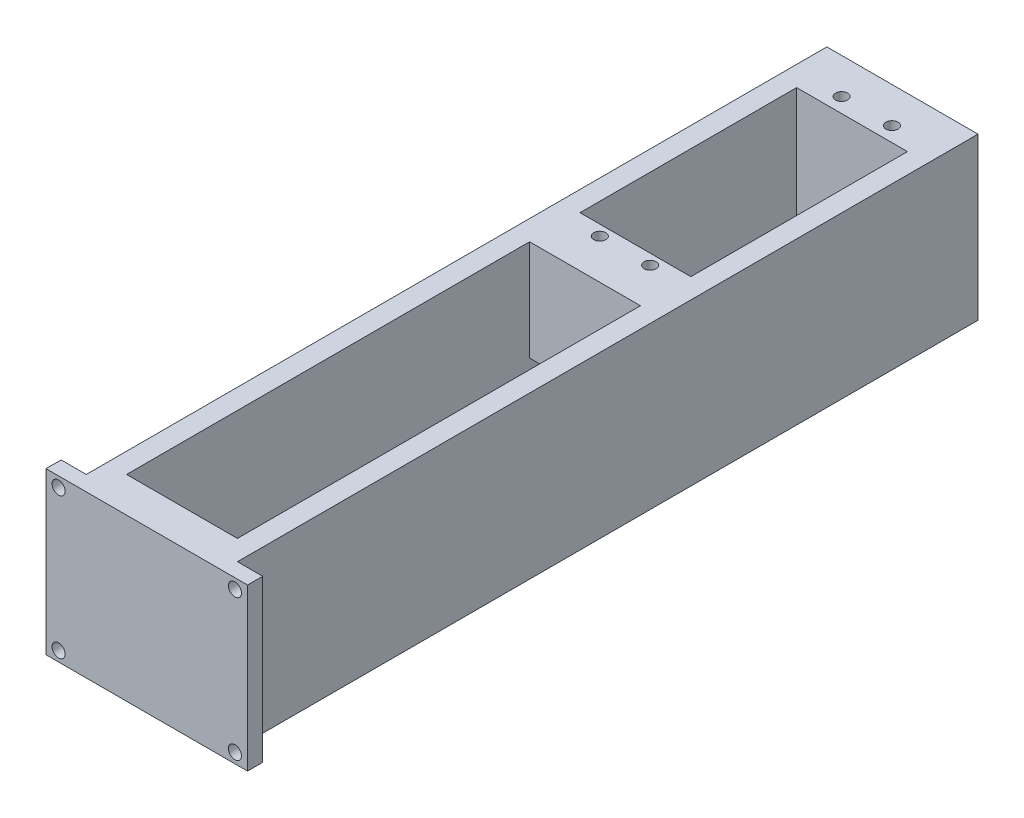
SolidWorks part; units mm, degrees
ref_plane "Front Plane" through (0, 0, 0) normal (0, 0, 1) x (1, 0, 0)
ref_plane "Top Plane" through (0, 0, 0) normal (0, 1, 0) x (1, 0, 0)
ref_plane "Right Plane" through (0, 0, 0) normal (1, 0, 0) x (0, 0, -1)
sketch "Sketch1" plane through (0, 0, 0) normal (0, 1, 0) x (1, 0, 0)
  line L1 (0, 0) -> (30, 0)
  line L2 (0, 0) -> (0, 150)
  line L3 (0, 150) -> (30, 150)
  line L4 (30, 0) -> (30, 150)
  dimension "D1" = 30
  dimension "D2" = 150
extrude "Boss-Extrude1" add sketch "Sketch1" along normal blind 40
sketch "Sketch2" plane through (0, 40, 0) normal (0, 1, 0) x (1, 0, 0)
  line L0 (30, 150) -> (0, 150) construction
  line L1 (4, 140) -> (26, 140)
  line L2 (4, 140) -> (4, 97)
  line L3 (4, 97) -> (26, 97)
  line L4 (26, 140) -> (26, 97)
  line L5 (0, 150) -> (0, 0) construction
  dimension "D1" = 22
  dimension "D2" = 43
  dimension "D3" = 10
  dimension "D4" = 4
extrude "Cut-Extrude1" cut sketch "Sketch2" against normal blind 30 and the other way through all
sketch "Sketch4" plane through (0, 0, 0) normal (0, -1, 0) x (1, 0, 0)
  line L0 (4, -140) -> (4, -97) construction
  line L1 (4, -97) -> (26, -97)
  line L2 (4, -97) -> (4, -87)
  line L3 (4, -87) -> (26, -87)
  line L4 (26, -97) -> (26, -87)
  line L5 (4, -97) -> (26, -97) construction
  dimension "D1" = 10
  dimension "D2" = 22
extrude "Cut-Extrude2" cut sketch "Sketch4" against normal blind 20
sketch "Sketch5" plane through (0, 0, 0) normal (-1, 0, 0) x (0, 0, 1)
  line L0 (0, 40) -> (0, 0) construction
  line L1 (-150, 0) -> (0, 0)
  line L2 (-150, 0) -> (-150, 8)
  line L3 (-150, 8) -> (0, 8)
  line L4 (0, 0) -> (0, 8)
  dimension "D1" = 8
extrude "Cut-Extrude3" cut sketch "Sketch5" against normal through all both and the other way through all
sketch "Sketch6" plane through (0, 40, 0) normal (0, 1, 0) x (1, 0, 0)
  line L0 (0, 150) -> (0, 0) construction
  circle A0 centre (10, 142.9247) radius 1.2
  circle A1 centre (20, 142.9247) radius 1.2
  circle A2 centre (10, 94.9247) radius 1.2
  circle A3 centre (20, 94.9247) radius 1.2
  dimension "D1" = 10
  dimension "D2" = 48
  dimension "D3" = 10
  dimension "D4" = 10
extrude "Cut-Extrude4" cut sketch "Sketch6" against normal blind 10
sketch "Sketch7" plane through (0, 0, 0) normal (0, 0, 1) x (1, 0, 0)
  line L1 (-5, 40) -> (35, 40)
  line L2 (-5, 40) -> (-5, 8)
  line L3 (-5, 8) -> (35, 8)
  line L4 (35, 40) -> (35, 8)
  line L6 (0, -17.6) -> (0, 17.6) construction
  line L8 (0, 40) -> (30, 40) construction
  dimension "D1" = 32
  dimension "D2" = 40
  dimension "D3" = 5
  dimension "D4" = 0
extrude "Boss-Extrude2" add sketch "Sketch7" against normal blind 3
sketch "Sketch8" plane through (0, 0, -3) normal (0, 0, -1) x (-1, 0, 0)
  line L0 (-35, 8) -> (-35, 40) construction
  line L1 (-30, 8) -> (-35, 8) construction
  circle A0 centre (-32.5, 38) radius 1.3
  circle A1 centre (-32.5, 10) radius 1.3
  circle A2 centre (2.5, 38) radius 1.3
  circle A3 centre (2.5, 10) radius 1.3
  dimension "D1" = 28
  dimension "D2" = 28
  dimension "D3" = 35
  dimension "D4" = 35
  dimension "D5" = 2.5
  dimension "D6" = 2
extrude "Cut-Extrude5" cut sketch "Sketch8" against normal through all
sketch "Sketch9" plane through (0, 40, 0) normal (0, 1, 0) x (1, 0, 0)
  line L0 (0, -17.6) -> (0, 17.6) construction
  line L1 (4, 87) -> (26, 87)
  line L2 (4, 87) -> (4, 7)
  line L3 (4, 7) -> (26, 7)
  line L4 (26, 87) -> (26, 7)
  line L7 (35, 3) -> (30, 3) construction
  dimension "D1" = 22
  dimension "D2" = 80
  dimension "D3" = 4
  dimension "D4" = 4
extrude "Cut-Extrude6" cut sketch "Sketch9" against normal through all
